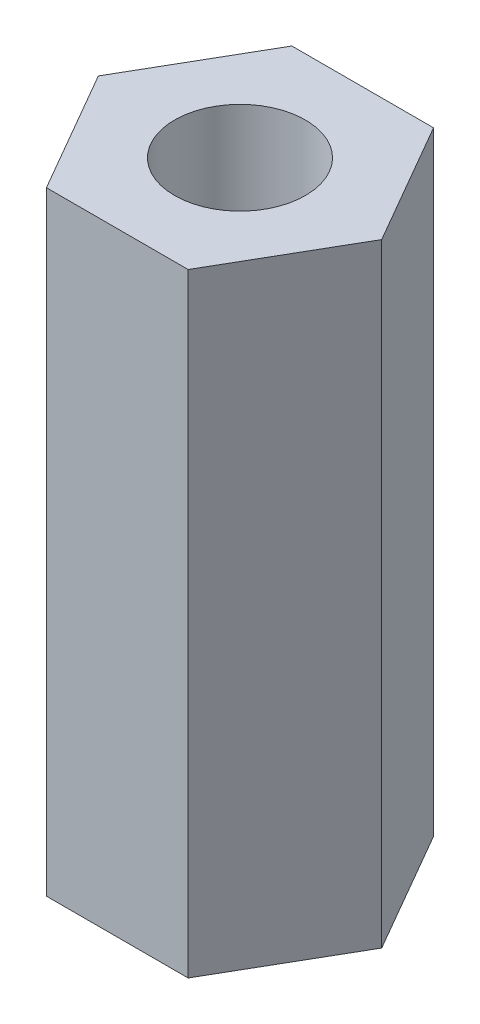
SolidWorks part; units mm, degrees
material "黄铜"
ref_plane "前视基准面" through (0, 0, 0) normal (0, 0, 1) x (1, 0, 0)
ref_plane "上视基准面" through (0, 0, 0) normal (0, 1, 0) x (1, 0, 0)
ref_plane "右视基准面" through (0, 0, 0) normal (1, 0, 0) x (0, 0, -1)
sketch "草图1" plane through (0, 0, 0) normal (0, 1, 0) x (1, 0, 0)
  line L1 (3.4641, 0) -> (1.7321, 3)
  line L2 (1.7321, 3) -> (-1.7321, 3)
  line L3 (-1.7321, 3) -> (-3.4641, 0)
  line L4 (-3.4641, 0) -> (-1.7321, -3)
  line L5 (-1.7321, -3) -> (1.7321, -3)
  line L6 (1.7321, -3) -> (3.4641, 0)
  circle A0 centre (0, 0) radius 3 construction
  circle A1 centre (0, 0) radius 1.6
  dimension "D1" = 6
  dimension "D2" = 3.2
extrude "凸台-拉伸1" add sketch "草图1" along normal blind 15
cosmetic thread "装饰螺纹线1" parameters "D2"=4
